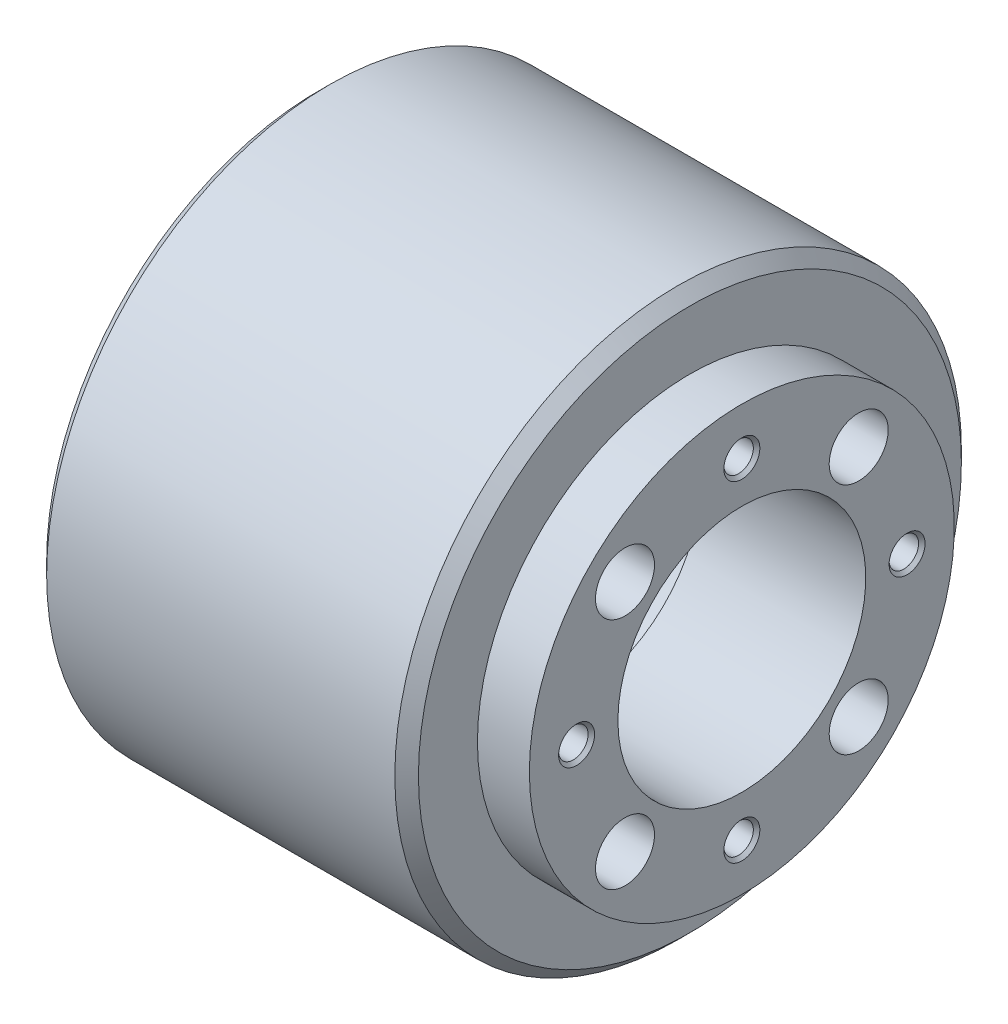
SolidWorks part; units mm, degrees
material "2014 Alloy"
ref_plane "Front Plane" through (0, 0, 0) normal (0, 0, 1) x (1, 0, 0)
ref_plane "Top Plane" through (0, 0, 0) normal (0, 1, 0) x (1, 0, 0)
ref_plane "Right Plane" through (0, 0, 0) normal (1, 0, 0) x (0, 0, -1)
sketch "Sketch1" plane through (0, 0, 0) normal (0, 1, 0) x (1, 0, 0)
  line L0 (0, 24) -> (31.5, 24)
  line L1 (31.5, 24) -> (31.5, 18)
  line L2 (31.5, 18) -> (35.9, 18)
  line L3 (35.9, 18) -> (35.9, 15)
  line L4 (21.9, 15) -> (21.9, 10.5)
  line L5 (0, 19.5) -> (0, 24)
  line L6 (0, 0) -> (28.2243, 0) construction
  line L7 (5.4, 15) -> (21.9, 15)
  line L8 (21.9, 10.5) -> (35.9, 10.5)
  line L9 (35.9, 10.5) -> (35.9, 15)
  line L11 (5.4, 15) -> (5.4, 19.5)
  line L12 (5.4, 19.5) -> (0, 19.5)
  dimension "D1" = 48
  dimension "D2" = 36
  dimension "D3" = 35.9
  dimension "D4" = 4.4
  dimension "D5" = 21
  dimension "D6" = 30
  dimension "D7" = 16.5
  dimension "D9" = 39
  dimension "D10" = 5.4
revolve "Revolve1" add sketch "Sketch1" angle 360 about L6
chamfer "Chamfer1" distance 1 angle 45 5 edges at (0, 0, 24) (31.5, 0, 24) (5.4, 0, 19.5) (5.4, 0, 15) (0, 0, 19.5)
hole_wizard "M3 Tapped Hole1" positions "Sketch4" profile "Sketch3" tap size "M3" standard "ISO"
sketch "Sketch4" plane through (35.9, 0, 0) normal (1, 0, 0) x (0, 0, -1)
  circle A0 centre (0, 0) radius 14
  point P0 (0, 14)
  point P2 (14, 0)
  point P4 (0, -14)
  point P6 (-14, 0)
  dimension "D1" = 28
sketch "Sketch3" plane through (35.9, 14, 0) normal (0, 1, 0) x (0, 0, -1)
  line L0 (0, 0) -> (0, 11.7511)
  line L1 (0, 11.7511) -> (1.25, 11)
  line L2 (1.25, 11) -> (1.25, 0.275)
  line L3 (1.25, 0.275) -> (1.525, 0)
  line L5 (1.525, 0) -> (0, 0)
  line L6 (-1.25, 0.275) -> (-1.525, 0) construction
  line L10 (0, 11.7511) -> (-1.25, 11) construction
  line L11 (0, -6.35) -> (0, 107.95) construction
  dimension "Tap Drill Dia." = 2.5
  dimension "Tap Drill Depth" = 11
  dimension "Near C'Sink Dia." = 3.05
  dimension "Near C'Sink Angle" = 90
  dimension "Drill Angle" = 118
sketch "Sketch6" plane through (35.9, 0, 0) normal (1, 0, 0) x (0, 0, -1)
  line L0 (-9.8995, 9.8995) -> (0, 0) construction
  line L1 (0, 0) -> (0, 9.8995) construction
  line L2 (0, 9.8995) -> (-9.8995, 9.8995) construction
  circle A0 centre (-9.8995, 9.8995) radius 2.5
  circle A1 centre (9.8995, 9.8995) radius 2.5
  circle A2 centre (-9.8995, -9.8995) radius 2.5
  circle A3 centre (9.8995, -9.8995) radius 2.5
  dimension "D1" = 5
  dimension "D2" = 14
extrude "Cut-Extrude1" cut sketch "Sketch6" against normal blind 10
